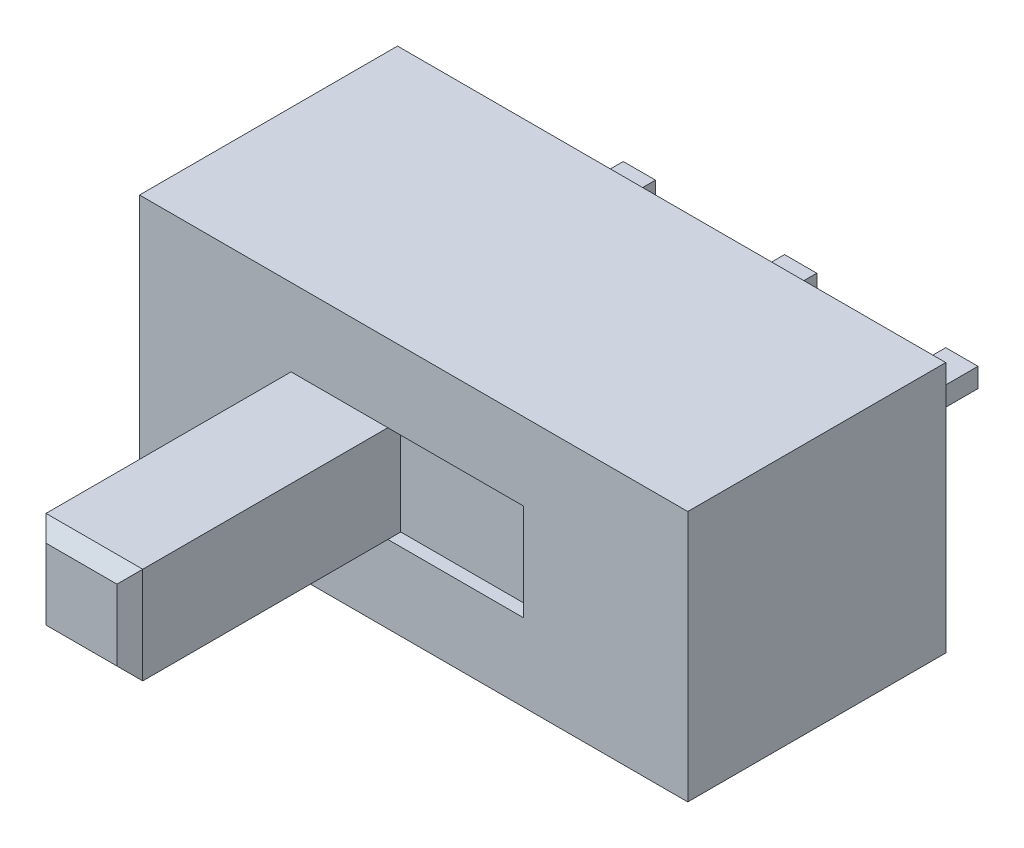
SolidWorks part; units mm, degrees
ref_plane "Front Plane" through (0, 0, 0) normal (0, 0, 1) x (1, 0, 0)
ref_plane "Top Plane" through (0, 0, 0) normal (0, 1, 0) x (1, 0, 0)
ref_plane "Right Plane" through (0, 0, 0) normal (1, 0, 0) x (0, 0, -1)
sketch "Sketch1" plane through (0, 0, 0) normal (0, 0, 1) x (1, 0, 0)
  line L1 (-4.25, 1.95) -> (4.25, 1.95)
  line L2 (-4.25, 1.95) -> (-4.25, -1.95)
  line L3 (-4.25, -1.95) -> (4.25, -1.95)
  line L4 (4.25, 1.95) -> (4.25, -1.95)
  line L5 (-4.25, 1.95) -> (4.25, -1.95) construction
  line L6 (-4.25, -1.95) -> (4.25, 1.95) construction
  point P0 (0, 0)
  dimension "D1" = 8.5
  dimension "D2" = 3.9
extrude "Boss-Extrude1" add sketch "Sketch1" along normal blind 4
sketch "Sketch2" plane through (0, 0, 4) normal (0, 0, 1) x (1, 0, 0)
  line L0 (0, 0) -> (-1.15, 0) construction
  line L2 (-1.9, 0.75) -> (-0.4, 0.75)
  line L3 (-1.9, 0.75) -> (-1.9, -0.75)
  line L4 (-1.9, -0.75) -> (-0.4, -0.75)
  line L5 (-0.4, 0.75) -> (-0.4, -0.75)
  line L6 (-1.9, 0.75) -> (-0.4, -0.75) construction
  line L7 (-1.9, -0.75) -> (-0.4, 0.75) construction
  dimension "D1" = 1.5
  dimension "D2" = 1.15
extrude "Boss-Extrude2" add sketch "Sketch2" along normal blind 4
chamfer "Chamfer1" distance 0.2 angle 45 4 edges at (-0.4, 0, 8) (-1.15, 0.75, 8) (-1.9, 0, 8) (-1.15, -0.75, 8)
sketch "Sketch3" plane through (0, 0, 4) normal (0, 0, 1) x (1, 0, 0)
  line L1 (-0.4, 0.75) -> (1.7, 0.75)
  line L2 (-0.4, 0.75) -> (-0.4, -0.75)
  line L3 (-0.4, -0.75) -> (1.7, -0.75)
  line L4 (1.7, 0.75) -> (1.7, -0.75)
  point P5 (0, 0)
  dimension "D1" = 1.7
extrude "Cut-Extrude1" cut sketch "Sketch3" against normal blind 0.2
sketch "Sketch4" plane through (0, 0, 0) normal (0, 0, -1) x (-1, 0, 0)
  line L0 (0, 0) -> (0, 1.95) construction
  line L1 (-0.25, 0.15) -> (0.25, 0.15)
  line L2 (-0.25, 0.15) -> (-0.25, -0.15)
  line L3 (-0.25, -0.15) -> (0.25, -0.15)
  line L4 (0.25, 0.15) -> (0.25, -0.15)
  line L5 (-0.25, 0.15) -> (0.25, -0.15) construction
  line L6 (-0.25, -0.15) -> (0.25, 0.15) construction
  line L7 (2.25, 0.15) -> (2.75, 0.15)
  line L8 (2.25, 0.15) -> (2.25, -0.15)
  line L9 (2.25, -0.15) -> (2.75, -0.15)
  line L10 (2.75, 0.15) -> (2.75, -0.15)
  line L11 (-4.25, 1.95) -> (4.25, 1.95) construction
  line L12 (-2.75, 0.15) -> (-2.75, -0.15)
  line L13 (-2.25, -0.15) -> (-2.75, -0.15)
  line L14 (-2.25, 0.15) -> (-2.25, -0.15)
  line L15 (-2.25, 0.15) -> (-2.75, 0.15)
  point P0 (0, 0)
  point P18 (2.5, -0.15)
  dimension "D1" = 0.5
  dimension "D2" = 0.3
  dimension "D3" = 2.5
extrude "Boss-Extrude3" add sketch "Sketch4" along normal blind 2
